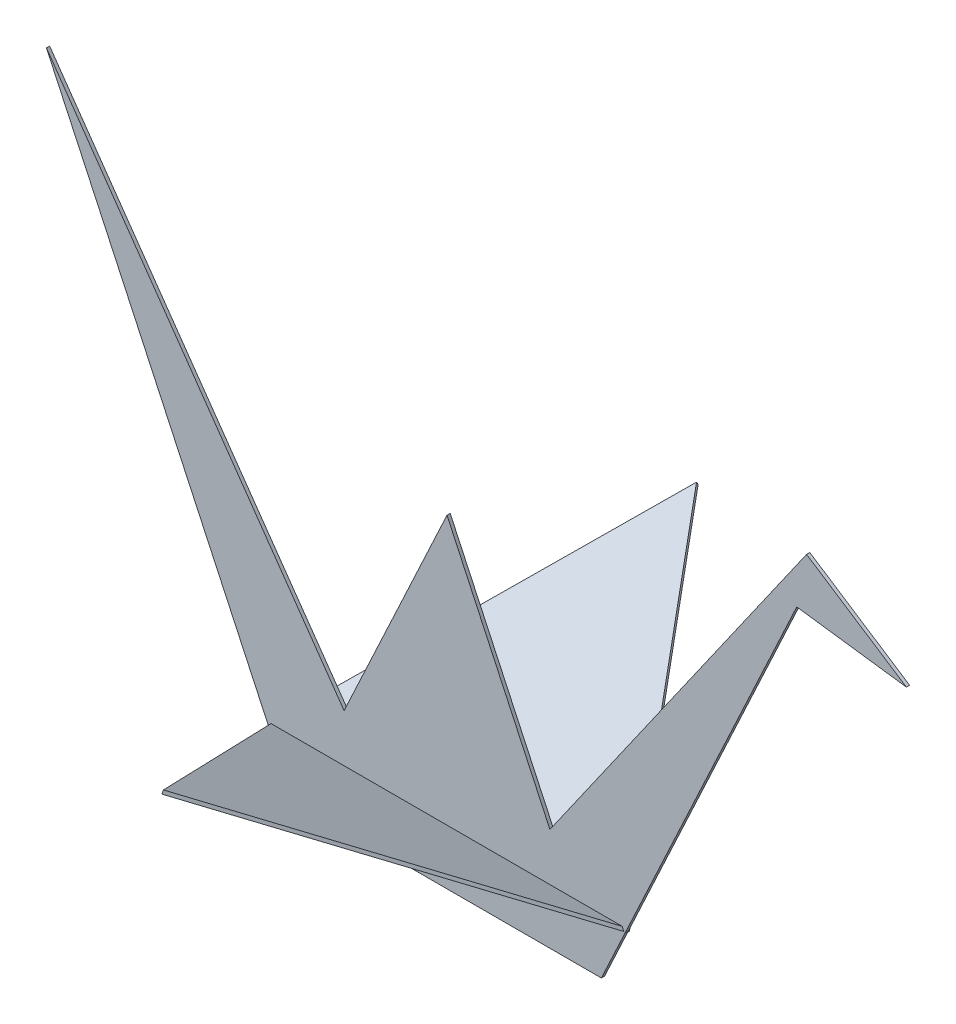
SolidWorks part; units mm, degrees
ref_plane "Front Plane" through (0, 0, 0) normal (0, 0, 1) x (1, 0, 0)
ref_plane "Top Plane" through (0, 0, 0) normal (0, 1, 0) x (1, 0, 0)
ref_plane "Right Plane" through (0, 0, 0) normal (1, 0, 0) x (0, 0, -1)
sketch "Sketch1" plane through (0, 0, 0) normal (0, 0, 1) x (1, 0, 0)
  line L0 (-304.8, 0) -> (304.8, 0)
  line L1 (304.8, 0) -> (690.6593, 827.4779)
  line L2 (690.6593, 827.4779) -> (907.0616, 798.5495)
  line L3 (907.0616, 798.5495) -> (710.0196, 927.0134)
  line L4 (710.0196, 927.0134) -> (203.2, 203.2)
  line L5 (203.2, 203.2) -> (0, 638.9638)
  line L6 (0, 638.9638) -> (-203.2, 203.2)
  line L7 (-203.2, 203.2) -> (-791.0086, 1042.6776)
  line L8 (-791.0086, 1042.6776) -> (-304.8, 0)
  line L9 (0, 638.9638) -> (0, 0) construction
  line L10 (-352.1769, 101.6) -> (352.1769, 101.6) construction
  line L11 (203.2, 203.2) -> (203.2, 0) construction
  point P14 (203.2, 101.6)
  dimension "D1" = 609.6
  dimension "D2" = 101.6
  dimension "D3" = 115
  dimension "D4" = 10
  dimension "D5" = 203.2
extrude "Boss-Extrude1" add sketch "Sketch1" along normal blind 6.35
ref_plane "Plane1" through (0, 76.2, 43.9941) normal (0, 0.866, 0.5) x (1, 0, 0)
sketch "Sketch2" plane through (0, 76.2, 43.9941) normal (0, 0.866, 0.5) x (1, 0, 0)
  line L0 (-352.1769, 50.8) -> (-40.027, 660.4)
  line L1 (-40.027, 660.4) -> (352.1769, 50.8)
  line L2 (-40.027, 660.4) -> (0, 50.8) construction
  line L3 (-352.1769, 50.8) -> (352.1769, 50.8) construction
  line L4 (0, 319.4819) -> (0, 0) construction
  line L5 (352.1769, 50.8) -> (-352.1769, 50.8)
  dimension "D1" = 609.6
extrude "Boss-Extrude2" add sketch "Sketch2" along normal mid plane 6.35
mirror "Mirror1" about plane through (0, 0, 0) normal (0, 0, 1) of "Boss-Extrude2"
